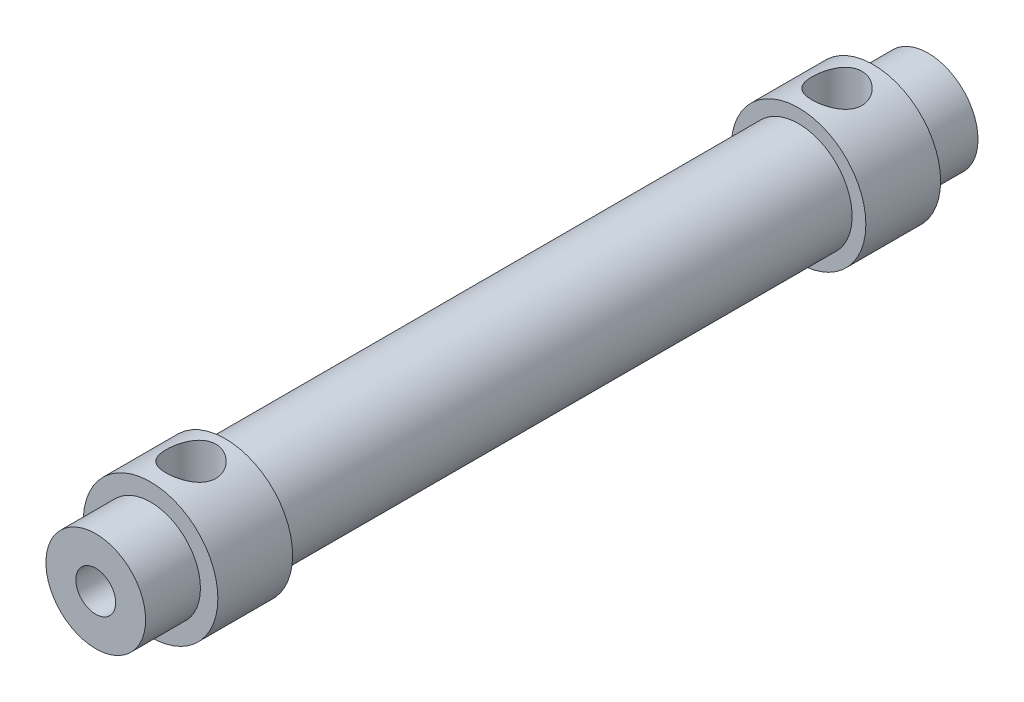
SolidWorks part; units mm, degrees
ref_plane "前视基准面" through (0, 0, 0) normal (0, 0, 1) x (1, 0, 0)
ref_plane "上视基准面" through (0, 0, 0) normal (0, 1, 0) x (1, 0, 0)
ref_plane "右视基准面" through (0, 0, 0) normal (1, 0, 0) x (0, 0, -1)
sketch "草图1" plane through (0, 0, 0) normal (0, 0, 1) x (1, 0, 0)
  circle A0 centre (0, 0) radius 10.75
  circle A1 centre (0, 0) radius 9
  dimension "D1" = 21.5
  dimension "D2" = 18
extrude "拉伸1" add sketch "草图1" along normal blind 115
sketch "草图2" plane through (0, 0, 115) normal (0, 0, 1) x (1, 0, 0)
  circle A0 centre (0, 0) radius 13.5
  dimension "D1" = 27
extrude "拉伸2" add sketch "草图2" along normal blind 15
sketch "草图3" plane through (0, 0, 130) normal (0, 0, 1) x (1, 0, 0)
  circle A0 centre (0, 0) radius 10
  dimension "D1" = 20
extrude "拉伸3" add sketch "草图3" along normal blind 11
ref_plane "基准面1" through (0, 0, 57.5) normal (0, 0, -1) x (-1, 0, 0)
sketch "草图4" plane through (0, 0, 141) normal (0, 0, 1) x (1, 0, 0)
  circle A0 centre (0, 0) radius 4
  dimension "D1" = 8
extrude "拉伸4" cut sketch "草图4" against normal through all
mirror "镜向2" about plane through (0, 0, 57.5) normal (0, 0, -1) of "拉伸2", "拉伸3", "拉伸4"
ref_plane "基准面2" through (0, 13.5, 0) normal (0, 1, 0) x (-1, 0, 0)
sketch "草图5" plane through (0, 13.5, 0) normal (0, 1, 0) x (-1, 0, 0)
  circle A0 centre (0, 121.893) radius 5
  circle A1 centre (0, -7.7089) radius 5
  dimension "D1" = 10
extrude "拉伸5" cut sketch "草图5" against normal blind 15
